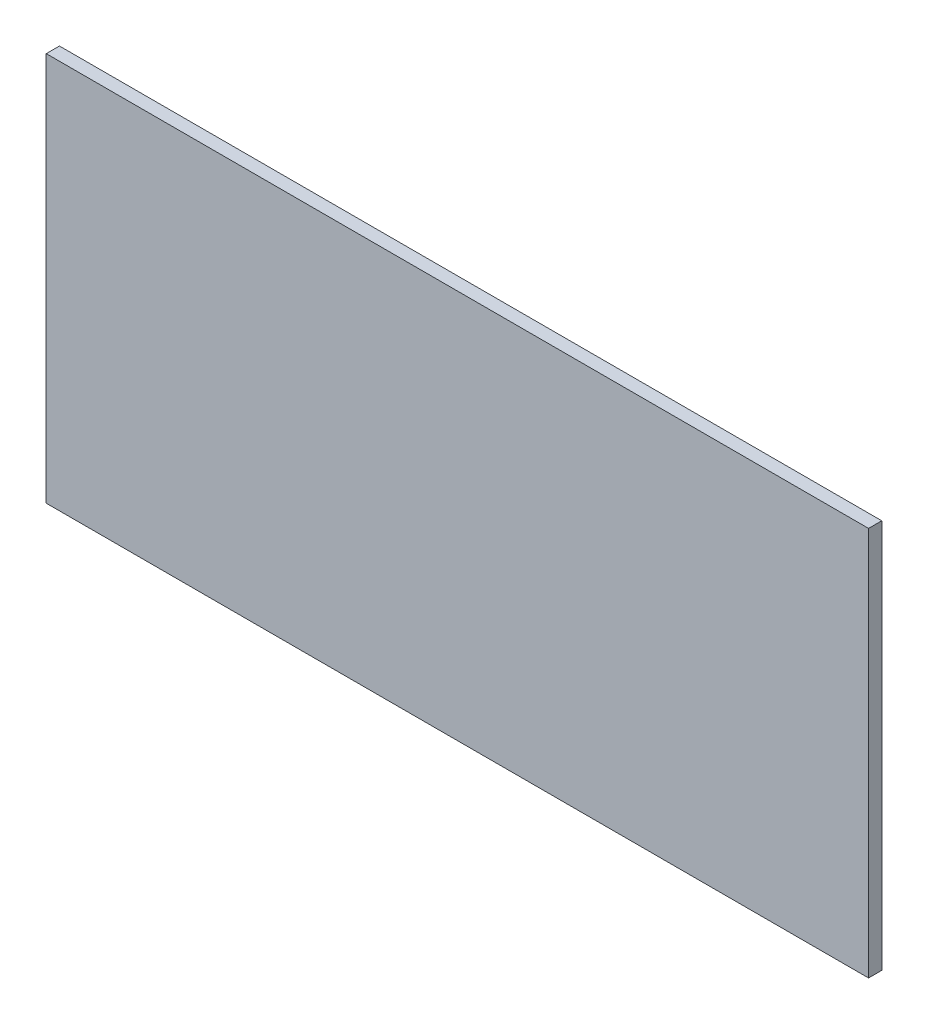
SolidWorks part; units mm, degrees
ref_plane "Спереди" through (0, 0, 0) normal (0, 0, 1) x (1, 0, 0)
ref_plane "Сверху" through (0, 0, 0) normal (0, 1, 0) x (1, 0, 0)
ref_plane "Справа" through (0, 0, 0) normal (1, 0, 0) x (0, 0, -1)
sketch "Эскиз1" plane through (0, 0, 0) normal (0, 0, 1) x (1, 0, 0)
  line L0 (25.25, -11.75) -> (25.25, 11.75) construction
  line L1 (28.25, -14.75) -> (-34.05, -14.75)
  line L2 (28.25, -14.75) -> (28.25, 14.75)
  line L3 (28.25, 14.75) -> (-34.05, 14.75)
  line L4 (-34.05, -14.75) -> (-34.05, 14.75)
  line L5 (-31.05, -0.741) -> (-31.05, 11.559) construction
  line L6 (9, -11.75) -> (25.25, -11.75) construction
  line L7 (25.25, 11.75) -> (9, 11.75) construction
  point P0 (0, 0)
  dimension "D1" = 3
  dimension "D2" = 3
  dimension "D3" = 3
  dimension "D4" = 3
extrude "Бобышка-Вытянуть1" add sketch "Эскиз1" along normal blind 1
